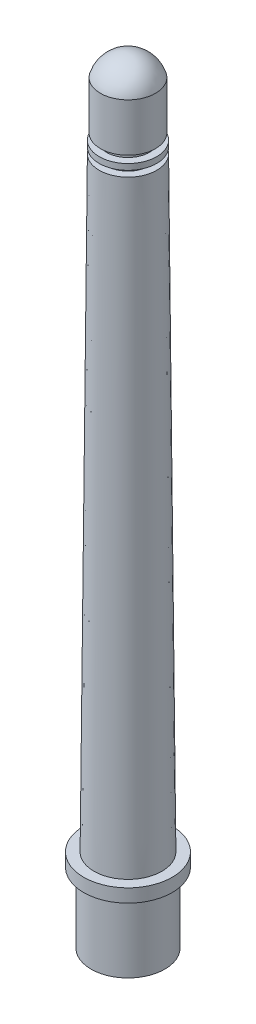
SolidWorks part; units mm, degrees
ref_plane "前视基准面" through (0, 0, 0) normal (0, 0, 1) x (1, 0, 0)
ref_plane "上视基准面" through (0, 0, 0) normal (0, 1, 0) x (1, 0, 0)
ref_plane "右视基准面" through (0, 0, 0) normal (1, 0, 0) x (0, 0, -1)
sketch "草图1" plane through (0, 0, 0) normal (0, 0, 1) x (1, 0, 0)
  line L0 (0, 100.775) -> (0, -11.8825) construction
  line L1 (-5, -9.5) -> (-5, 0)
  line L2 (-5, 0) -> (-6, 0)
  line L3 (-6, 0) -> (-6, 1.8)
  line L4 (-6, 1.8) -> (-4.6, 1.8)
  line L5 (-4.6, 1.8) -> (-3.9, 83.8)
  line L6 (-3.9, 83.8) -> (-2.9, 83.8)
  line L7 (-2.9, 86.2588) -> (-2.9, 85.4)
  line L8 (-2.9, 85.4) -> (-3.9, 85.4)
  line L9 (-3.9, 85.4) -> (-3.9, 84.6)
  line L10 (-3.9, 84.6) -> (-2.9, 84.6)
  line L11 (-2.9, 84.6) -> (-2.9, 83.8)
  line L12 (-2.9, 86.2588) -> (-3.7351, 86.2588)
  line L13 (-3.7351, 86.2588) -> (-3.7351, 92.7588)
  line L14 (-5, -9.5) -> (0, -9.5)
  line L15 (0, 95.5878) -> (0, -9.5)
  arc A0 (-3.7351, 92.7588) -> (0, 95.5878) centre (0, 91.7076) cw
  dimension "D1" = 5
  dimension "D2" = 9.5
  dimension "D3" = 1.8
  dimension "D4" = 6
  dimension "D5" = 4.6
  dimension "D6" = 82
  dimension "D7" = 3.9
  dimension "D10" = 0.8
  dimension "D11" = 0.8
  dimension "D12" = 6.5
revolve "旋转1" add sketch "草图1" angle 360 about L0
